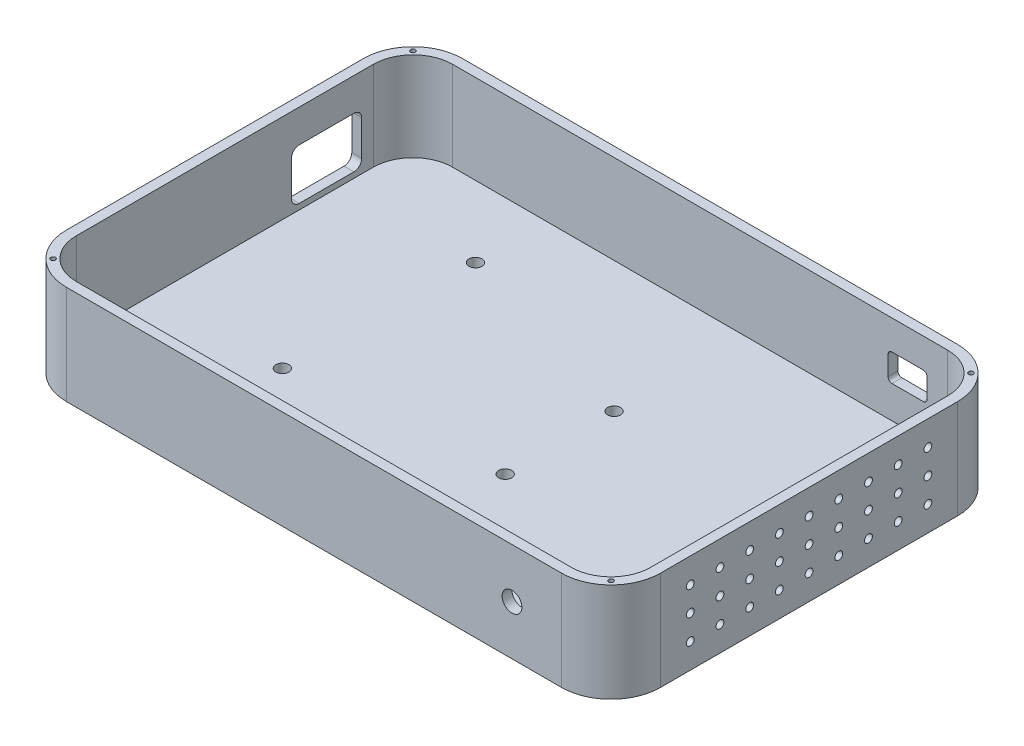
SolidWorks part; units mm, degrees
ref_plane "Front Plane" through (0, 0, 0) normal (0, 0, 1) x (1, 0, 0)
ref_plane "Top Plane" through (0, 0, 0) normal (0, 1, 0) x (1, 0, 0)
ref_plane "Right Plane" through (0, 0, 0) normal (1, 0, 0) x (0, 0, -1)
sketch "Sketch1" plane through (0, 0, 0) normal (0, 1, 0) x (1, 0, 0)
  line L1 (63.5, 50.8) -> (-63.5, 50.8)
  line L2 (76.2, 38.1) -> (76.2, -38.1)
  line L3 (63.5, -50.8) -> (-63.5, -50.8)
  line L4 (-76.2, 38.1) -> (-76.2, -38.1)
  line L5 (76.2, 50.8) -> (-76.2, -50.8) construction
  line L6 (76.2, -50.8) -> (-76.2, 50.8) construction
  arc A0 (63.5, -50.8) -> (76.2, -38.1) centre (63.5, -38.1) ccw
  arc A1 (-63.5, -50.8) -> (-76.2, -38.1) centre (-63.5, -38.1) cw
  arc A2 (63.5, 50.8) -> (76.2, 38.1) centre (63.5, 38.1) cw
  arc A3 (-63.5, 50.8) -> (-76.2, 38.1) centre (-63.5, 38.1) ccw
  point P0 (0, 0)
  dimension "D3" = 12.7
  dimension "D1" = 152.4
  dimension "D2" = 101.6
extrude "Boss-Extrude1" add sketch "Sketch1" along normal blind 25.4
sketch "Sketch4" plane through (0, 25.4, 0) normal (0, 1, 0) x (1, 0, 0)
  line L0 (-63.5, 48.26) -> (63.5, 48.26)
  line L1 (73.66, 38.1) -> (73.66, -38.1)
  line L2 (63.5, -48.26) -> (-63.5, -48.26)
  line L3 (-73.66, -38.1) -> (-73.66, 38.1)
  line L4 (-76.2, 38.1) -> (-76.2, -38.1) construction
  line L5 (63.5, 50.8) -> (-63.5, 50.8) construction
  line L6 (-63.5, -50.8) -> (63.5, -50.8) construction
  line L7 (76.2, -38.1) -> (76.2, 38.1) construction
  arc A0 (73.66, 38.1) -> (63.5, 48.26) centre (63.5, 38.1) ccw
  arc A1 (63.5, -48.26) -> (73.66, -38.1) centre (63.5, -38.1) ccw
  arc A2 (-63.5, -48.26) -> (-73.66, -38.1) centre (-63.5, -38.1) cw
  arc A3 (-73.66, 38.1) -> (-63.5, 48.26) centre (-63.5, 38.1) cw
  dimension "D5" = 10.16
  dimension "D1" = 2.54
  dimension "D2" = 2.54
  dimension "D3" = 2.54
  dimension "D4" = 2.54
extrude "Cut-Extrude6" cut sketch "Sketch4" against normal blind 22.86
sketch "Sketch7" plane through (0, 25.4, 0) normal (0, 1, 0) x (1, 0, 0)
  line L0 (-73.66, 38.1) -> (-73.66, -38.1) construction
  line L1 (63.5, 48.26) -> (-63.5, 48.26) construction
  line L2 (-63.5, -48.26) -> (63.5, -48.26) construction
  line L3 (-63.5, -48.26) -> (63.5, -48.26) construction
  line L4 (73.66, -38.1) -> (73.66, 38.1) construction
  line L5 (63.5, 48.26) -> (-63.5, 48.26) construction
  circle A0 centre (-71.56, 46.16) radius 0.6
  circle A1 centre (-71.56, -46.16) radius 0.6
  circle A2 centre (71.56, -46.16) radius 0.6
  circle A3 centre (71.56, 46.16) radius 0.6
  dimension "D1" = 1.2
  dimension "D4" = 1.2
  dimension "D7" = 1.2
  dimension "D10" = 1.2
  dimension "D2" = 2.1
  dimension "D3" = 2.1
  dimension "D5" = 2.1
  dimension "D6" = 2.1
  dimension "D8" = 2.1
  dimension "D9" = 2.1
  dimension "D11" = 2.1
  dimension "D12" = 2.1
extrude "Cut-Extrude8" cut sketch "Sketch7" against normal blind 2.46
sketch "Sketch10" plane through (-76.2, 0, 0) normal (-1, 0, 0) x (0, 0, 1)
  line L0 (-38.1, 0) -> (38.1, 0) construction
  line L1 (-33.1, 17) -> (-19.1, 17)
  line L2 (-35.1, 15) -> (-35.1, 6)
  line L3 (-33.1, 4) -> (-19.1, 4)
  line L4 (-17.1, 15) -> (-17.1, 6)
  line L5 (-38.1, 25.4) -> (-38.1, 0) construction
  arc A0 (-35.1, 6) -> (-33.1, 4) centre (-33.1, 6) ccw
  arc A1 (-17.1, 6) -> (-19.1, 4) centre (-19.1, 6) cw
  arc A2 (-19.1, 17) -> (-17.1, 15) centre (-19.1, 15) cw
  arc A3 (-35.1, 15) -> (-33.1, 17) centre (-33.1, 15) cw
  point P10 (-35.1, 4)
  point P13 (-17.1, 4)
  point P16 (-17.1, 17)
  dimension "D5" = 2
  dimension "D1" = 18
  dimension "D2" = 13
  dimension "D3" = 4
  dimension "D4" = 3
extrude "Cut-Extrude9" cut sketch "Sketch10" against normal blind 10
sketch "Sketch12" plane through (76.2, 0, 0) normal (1, 0, 0) x (0, 0, -1)
  line L0 (-38.1, 25.4) -> (38.1, 25.4) construction
  line L1 (-38.1, 0) -> (38.1, 0) construction
  line L2 (-30.48, 19) -> (30.48, 19) construction
  line L3 (-30.48, 12.7) -> (30.48, 12.7) construction
  line L4 (-30.48, 6.4) -> (30.48, 6.4) construction
  line L7 (-38.1, 25.4) -> (-38.1, 0) construction
  line L8 (38.1, 25.4) -> (38.1, 0) construction
  circle A0 centre (-30.48, 19) radius 1
  circle A1 centre (-30.48, 12.7) radius 1
  circle A2 centre (-30.48, 6.4) radius 1
  circle A3 centre (-22.86, 19) radius 1
  circle A4 centre (-22.86, 12.7) radius 1
  circle A5 centre (-22.86, 6.4) radius 1
  circle A6 centre (-15.24, 19) radius 1
  circle A7 centre (-15.24, 12.7) radius 1
  circle A8 centre (-15.24, 6.4) radius 1
  circle A9 centre (-7.62, 19) radius 1
  circle A10 centre (-7.62, 12.7) radius 1
  circle A11 centre (-7.62, 6.4) radius 1
  circle A12 centre (0, 19) radius 1
  circle A13 centre (0, 12.7) radius 1
  circle A14 centre (0, 6.4) radius 1
  circle A15 centre (7.62, 19) radius 1
  circle A16 centre (7.62, 12.7) radius 1
  circle A17 centre (7.62, 6.4) radius 1
  circle A18 centre (15.24, 19) radius 1
  circle A19 centre (15.24, 12.7) radius 1
  circle A20 centre (15.24, 6.4) radius 1
  circle A21 centre (22.86, 19) radius 1
  circle A22 centre (22.86, 12.7) radius 1
  circle A23 centre (22.86, 6.4) radius 1
  circle A27 centre (30.48, 19) radius 1
  circle A28 centre (30.48, 12.7) radius 1
  circle A29 centre (30.48, 6.4) radius 1
  dimension "D1" = 2
  dimension "D5" = 6.4
  dimension "D35" = 2
  dimension "D2" = 6.4
  dimension "D3" = 6.4
  dimension "D4" = 12.7
  dimension "D6" = 6.4
  dimension "D7" = 12.7
  dimension "D8" = 7.62
  dimension "D9" = 7.62
  dimension "D10" = 7.62
  dimension "D11" = 7.62
  dimension "D12" = 7.62
  dimension "D13" = 7.62
  dimension "D14" = 7.62
  dimension "D15" = 7.62
  dimension "D16" = 7.62
  dimension "D17" = 7.62
  dimension "D18" = 7.62
  dimension "D19" = 7.62
  dimension "D20" = 7.62
  dimension "D21" = 7.62
  dimension "D22" = 7.62
  dimension "D23" = 7.62
  dimension "D24" = 7.62
  dimension "D25" = 7.62
  dimension "D26" = 7.62
  dimension "D27" = 7.62
  dimension "D28" = 7.62
  dimension "D29" = 7.62
  dimension "D30" = 7.62
  dimension "D31" = 7.62
  dimension "D32" = 7.62
  dimension "D33" = 7.62
  dimension "D34" = 7.62
extrude "Cut-Extrude10" cut sketch "Sketch12" against normal blind 10
sketch "Sketch13" plane through (0, 0, -50.8) normal (0, 0, -1) x (-1, 0, 0)
  line L0 (-63.5, 25.4) -> (63.5, 25.4) construction
  line L1 (-57.2, 17.8397) -> (-49.2, 17.8397)
  line L2 (-58.2, 16.8397) -> (-58.2, 11.8397)
  line L3 (-57.2, 10.8397) -> (-49.2, 10.8397)
  line L4 (-48.2, 16.8397) -> (-48.2, 11.8397)
  line L5 (-76.2, 25.4) -> (-76.2, 0) construction
  arc A0 (-57.2, 10.8397) -> (-58.2, 11.8397) centre (-57.2, 11.8397) cw
  arc A1 (-49.2, 10.8397) -> (-48.2, 11.8397) centre (-49.2, 11.8397) ccw
  arc A2 (-49.2, 17.8397) -> (-48.2, 16.8397) centre (-49.2, 16.8397) cw
  arc A3 (-58.2, 16.8397) -> (-57.2, 17.8397) centre (-57.2, 16.8397) cw
  point P8 (-58.2, 10.8397)
  point P11 (-48.2, 10.8397)
  point P16 (-58.2, 17.8397)
  dimension "D4" = 1
  dimension "D1" = 10
  dimension "D2" = 7
  dimension "D3" = 7.5603
  dimension "D5" = 18
extrude "Cut-Extrude12" cut sketch "Sketch13" against normal blind 10
sketch "Sketch14" plane through (0, 2.54, 0) normal (0, 1, 0) x (1, 0, 0)
  line L0 (-63.5, -48.26) -> (63.5, -48.26) construction
  line L2 (-73.66, 38.1) -> (-73.66, -38.1) construction
  circle A0 centre (-39.37, 30) radius 1.6637
  circle A1 centre (-40.64, -18.26) radius 1.6637
  circle A2 centre (11.43, -13.18) radius 1.6637
  circle A3 centre (11.43, 14.76) radius 1.6637
  dimension "D1" = 50.8
  dimension "D3" = 52.07
  dimension "D4" = 27.94
  dimension "D5" = 5.08
  dimension "D6" = 30
  dimension "D8" = 33.02
  dimension "D2" = 48.26
extrude "Cut-Extrude13" cut sketch "Sketch14" against normal through all
sketch "Sketch15" plane through (0, 2.54, 0) normal (0, 1, 0) x (1, 0, 0)
  circle A0 centre (-27.4517, -37.4896) radius 1.925
extrude "Cut-Extrude14" cut sketch "Sketch15" against normal through all
sketch "Sketch16" plane through (0, 0, 50.8) normal (0, 0, 1) x (1, 0, 0)
  line L0 (-63.5, 25.4) -> (63.5, 25.4) construction
  line L2 (63.5, 25.4) -> (63.5, 0) construction
  circle A0 centre (50.8, 12.7) radius 2.54
  dimension "D1" = 5.08
  dimension "D2" = 12.7
  dimension "D3" = 12.7
extrude "Cut-Extrude15" cut sketch "Sketch16" against normal blind 5.08
